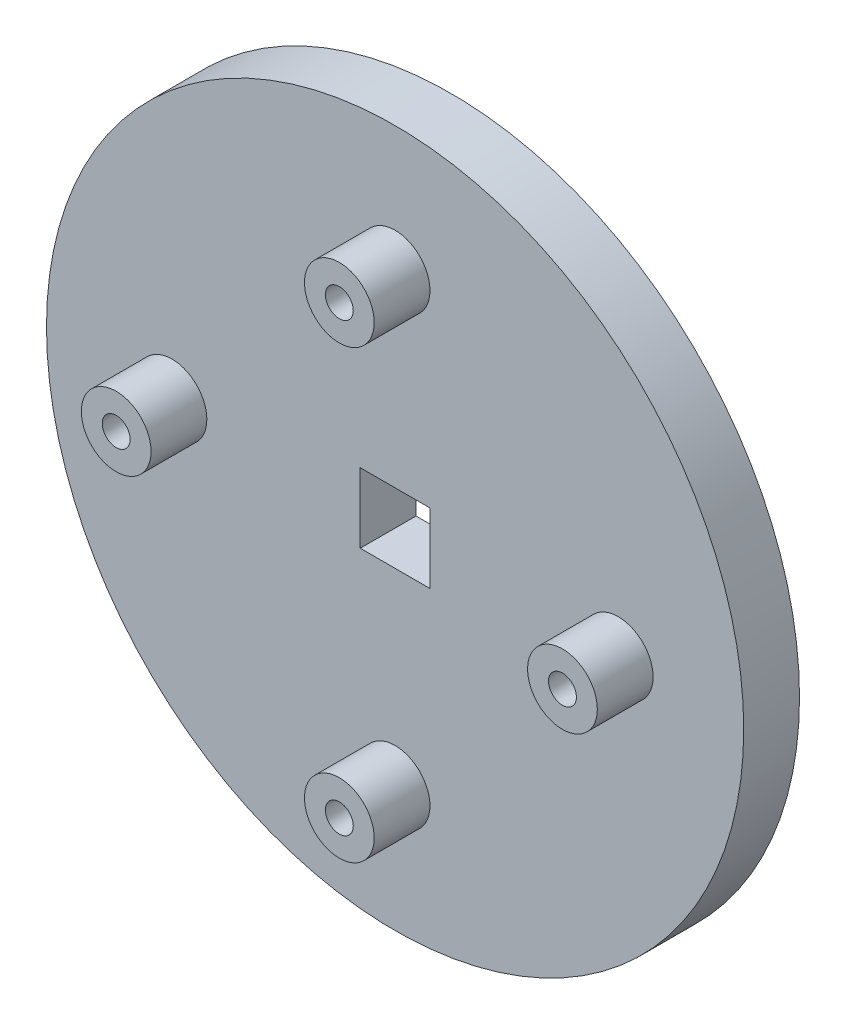
SolidWorks part; units mm, degrees
ref_plane "前视基准面" through (0, 0, 0) normal (0, 0, 1) x (1, 0, 0)
ref_plane "上视基准面" through (0, 0, 0) normal (0, 1, 0) x (1, 0, 0)
ref_plane "右视基准面" through (0, 0, 0) normal (1, 0, 0) x (0, 0, -1)
other "Configuration Table"
sketch "草图1" plane through (0, 0, 0) normal (0, 0, 1) x (1, 0, 0)
  circle A0 centre (0, 0) radius 50
  dimension "D1" = 100
extrude "凸台-拉伸1" add sketch "草图1" along normal blind 8
sketch "草图2" plane through (0, 0, 8) normal (0, 0, 1) x (1, 0, 0)
  line L1 (-5, -5) -> (5, -5)
  line L2 (-5, -5) -> (-5, 5)
  line L3 (-5, 5) -> (5, 5)
  line L4 (5, -5) -> (5, 5)
  line L5 (-5, -5) -> (5, 5) construction
  line L6 (-5, 5) -> (5, -5) construction
  point P0 (0, 0)
  dimension "D1" = 10
extrude "切除-拉伸1" cut sketch "草图2" against normal blind 8
sketch "草图3" plane through (0, 0, 8) normal (0, 0, 1) x (1, 0, 0)
  circle A0 centre (0, 0) radius 32
  circle A1 centre (0, 32) radius 5
  circle A2 centre (0, 32) radius 2
  circle A3 centre (32, 0) radius 5
  circle A4 centre (32, 0) radius 2
  circle A5 centre (0, -32) radius 5
  circle A6 centre (0, -32) radius 2
  circle A7 centre (-32, 0) radius 5
  circle A8 centre (-32, 0) radius 2
  point P18 (0, 0)
  dimension "D1" = 64
  dimension "D2" = 4
extrude "凸台-拉伸3" add sketch "草图3" along normal blind 8 contours A2 A0 A1 | A2 A0 A1 | A8 A0 A7 | A8 A0 A7 | A4 A0 A3 | A4 A0 A3 | A6 A0 A5 | A6 A0 A5
